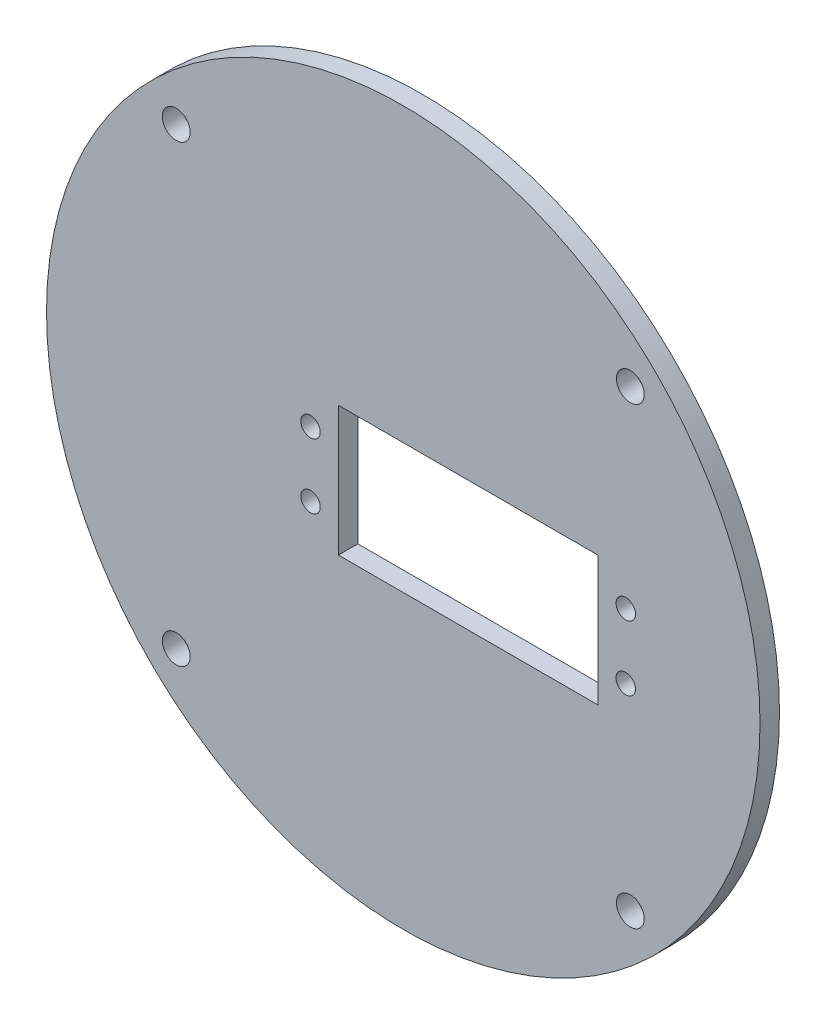
SolidWorks part; units mm, degrees
ref_plane "前视基准面" through (0, 0, 0) normal (0, 0, 1) x (1, 0, 0)
ref_plane "上视基准面" through (0, 0, 0) normal (0, 1, 0) x (1, 0, 0)
ref_plane "右视基准面" through (0, 0, 0) normal (1, 0, 0) x (0, 0, -1)
sketch "草图1" plane through (0, 0, 0) normal (0, 0, 1) x (1, 0, 0)
  line L0 (-35.0018, -35.0018) -> (35.0018, -35.0018)
  line L1 (-35.0018, -35.0018) -> (-35.0018, 35.0018)
  line L2 (-35.0018, 35.0018) -> (35.0018, 35.0018)
  line L3 (35.0018, -35.0018) -> (35.0018, 35.0018)
  line L4 (-35.0018, -35.0018) -> (35.0018, 35.0018) construction
  line L5 (-35.0018, 35.0018) -> (35.0018, -35.0018) construction
  line L7 (-10, 10) -> (30, 10)
  line L8 (-10, 10) -> (-10, -10)
  line L9 (-10, -10) -> (30, -10)
  line L10 (30, 10) -> (30, -10)
  line L11 (-14.3, 5) -> (34.3, 5)
  line L12 (-14.3, 5) -> (-14.3, -5)
  line L13 (-14.3, -5) -> (34.3, -5)
  line L14 (34.3, 5) -> (34.3, -5)
  circle A0 centre (0, 0) radius 55
  circle A1 centre (0, 0) radius 45
  circle A2 centre (-35.0018, 35.0018) radius 2.15
  circle A3 centre (35.0018, 35.0018) radius 2.15
  circle A4 centre (35.0018, -35.0018) radius 2.15
  circle A5 centre (-35.0018, -35.0018) radius 2.15
  circle A6 centre (-14.3, 5) radius 1.5
  circle A7 centre (-14.3, -5) radius 1.5
  circle A8 centre (34.3, 5) radius 1.5
  circle A9 centre (34.3, -5) radius 1.5
  point P16 (-10, 0)
  point P21 (-14.3, 0)
  point P22 (10, 5)
  point P23 (10, 10)
  dimension "D1" = 90
  dimension "D3" = 4.3
  dimension "D4" = 4.3
  dimension "D5" = 4.3
  dimension "D6" = 4.3
  dimension "D7" = 110
  dimension "D14" = 3
  dimension "D15" = 3
  dimension "D16" = 3
  dimension "D17" = 3
  dimension "D2" = 99
  dimension "D9" = 40
  dimension "D10" = 20
  dimension "D11" = 10
  dimension "D12" = 4.3
  dimension "D13" = 10
extrude "凸台-拉伸2" add sketch "草图1" along normal blind 3 contours A0 A5 L1 A1 A2 L2 A3 L3 A4 L0 | L1 A1 | A9 L13 L10 L9 L8 A7 L12 A6 L11 L7 A8 L3 A1 L2 L1 L0 | L2 A1 | A3 L2 A1 L3 | A9 L3 A1 A8 | L0 A1 | A5 L0 A1 L1 | A7 L13 L8 L11 A6 L12 | A2 L1 A1 L2 | A4 L3 A1 L0 | A9 L14 A8 L11 L10 L13 | A9 L3 A8 L14
